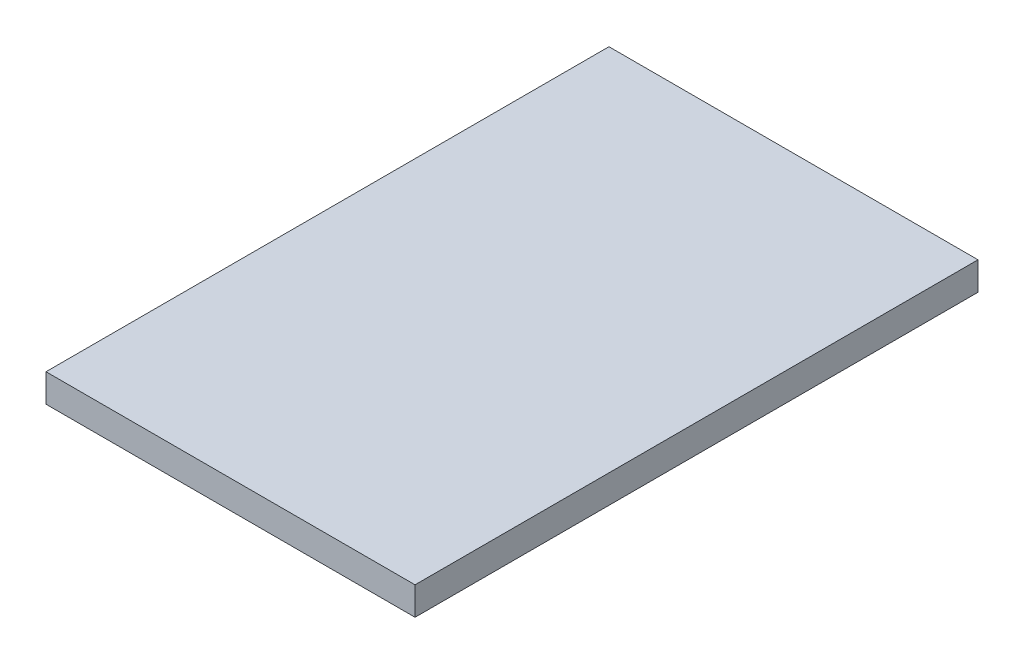
SolidWorks part; units mm, degrees
ref_plane "Alzado" through (0, 0, 0) normal (0, 0, 1) x (1, 0, 0)
ref_plane "Planta" through (0, 0, 0) normal (0, 1, 0) x (1, 0, 0)
ref_plane "Vista lateral" through (0, 0, 0) normal (1, 0, 0) x (0, 0, -1)
sketch "Croquis1" plane through (0, 0, 0) normal (0, 1, 0) x (1, 0, 0)
  line L1 (-118, 180) -> (118, 180)
  line L2 (-118, 180) -> (-118, -180)
  line L3 (-118, -180) -> (118, -180)
  line L4 (118, 180) -> (118, -180)
  line L5 (-118, 180) -> (118, -180) construction
  line L6 (-118, -180) -> (118, 180) construction
  point P0 (0, 0)
  dimension "D1" = 236
  dimension "D2" = 360
extrude "Saliente-Extruir1" add sketch "Croquis1" along normal blind 18
